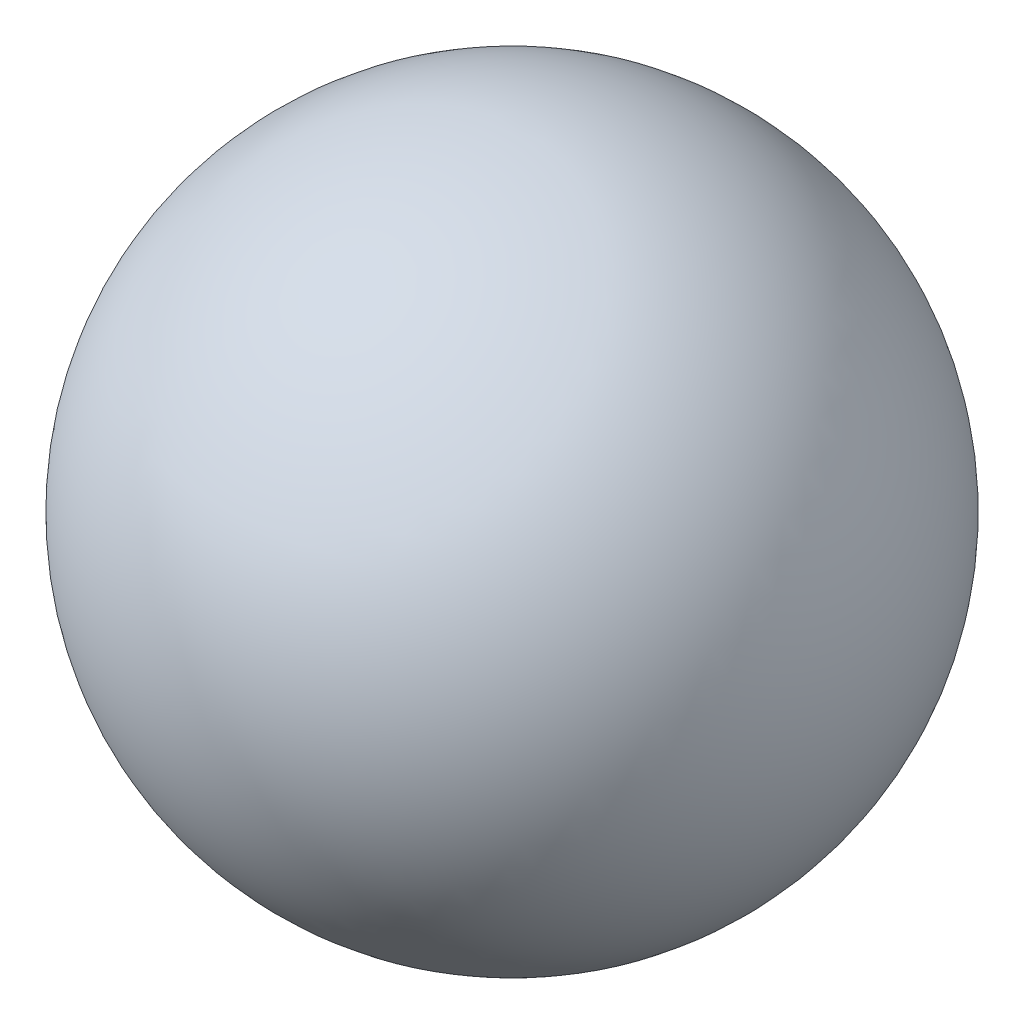
SolidWorks part; units mm, degrees
ref_plane "前视基准面" through (0, 0, 0) normal (0, 0, 1) x (1, 0, 0)
ref_plane "上视基准面" through (0, 0, 0) normal (0, 1, 0) x (1, 0, 0)
ref_plane "右视基准面" through (0, 0, 0) normal (1, 0, 0) x (0, 0, -1)
sketch "草图1" plane through (0, 0, 0) normal (0, 0, 1) x (1, 0, 0)
  line L0 (0, 8.5) -> (0, -8.5)
  arc A0 (0, -8.5) -> (0, 8.5) centre (0, 0) ccw
  dimension "D1" = 17
revolve "旋转1" add sketch "草图1" angle 360 about L0
sketch "草图2" plane through (0, 0, 0) normal (0, 0, 1) x (1, 0, 0)
  point P0 (0, 0)
  point P3 (0, 0)
